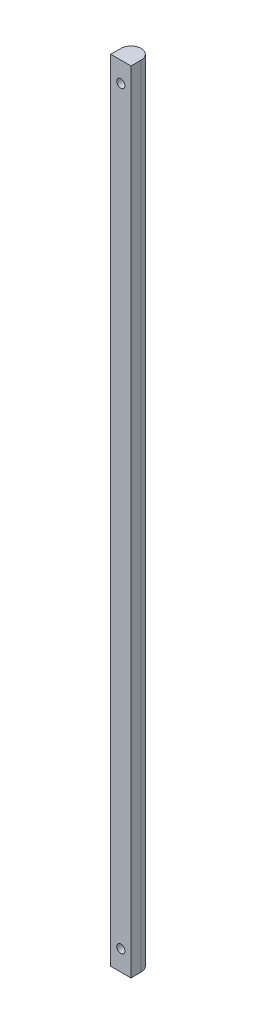
SolidWorks part; units mm, degrees
material "6061-T6 (SS)"
ref_plane "Front Plane" through (0, 0, 0) normal (0, 0, 1) x (1, 0, 0)
ref_plane "Top Plane" through (0, 0, 0) normal (0, 1, 0) x (1, 0, 0)
ref_plane "Right Plane" through (0, 0, 0) normal (1, 0, 0) x (0, 0, -1)
sketch "Sketch1" plane through (0, 0, 0) normal (0, 1, 0) x (1, 0, 0)
  line L0 (-3.175, 3.175) -> (-3.175, 0)
  line L1 (-3.175, 0) -> (3.175, 0)
  line L2 (3.175, 0) -> (3.175, 3.175)
  arc A0 (-3.175, 3.175) -> (3.175, 3.175) centre (0, 3.175) cw
  point P5 (0, 0)
  point P8 (0, 6.35)
  dimension "D2" = 3.175
  dimension "D1" = 6.35
  dimension "D3" = 6.35
extrude "Boss-Extrude1" add sketch "Sketch1" along normal mid plane 247.65
hole_wizard "#5-40 Tapped Hole1" positions "Sketch2" profile "Sketch3" tap size "#5-40" standard "ANSI Inch" end condition through all
sketch "Sketch2" plane through (0, 0, 0) normal (0, 0, 1) x (1, 0, 0)
  line L0 (-3.175, -123.825) -> (3.175, -123.825) construction
  line L1 (-3.175, 123.825) -> (3.175, 123.825) construction
  point P0 (0, 117.475)
  point P2 (0, -117.475)
  dimension "D1" = 6.35
  dimension "D2" = 6.35
sketch "Sketch3" plane through (0, 117.475, 0) normal (1, 0, 0) x (0, -1, 0)
  line L0 (0, 0) -> (0, 6.35)
  line L1 (0, 6.35) -> (1.289, 6.35)
  line L2 (1.289, 6.35) -> (1.289, 0)
  line L5 (1.289, 0) -> (0, 0)
  line L11 (0, -6.35) -> (0, 107.95) construction
  dimension "Thru Tap Drill Dia." = 2.5781
  dimension "Thru Tap Drill Depth" = 6.35
cosmetic thread "Hole Thread1"
cosmetic thread "Hole Thread2"
